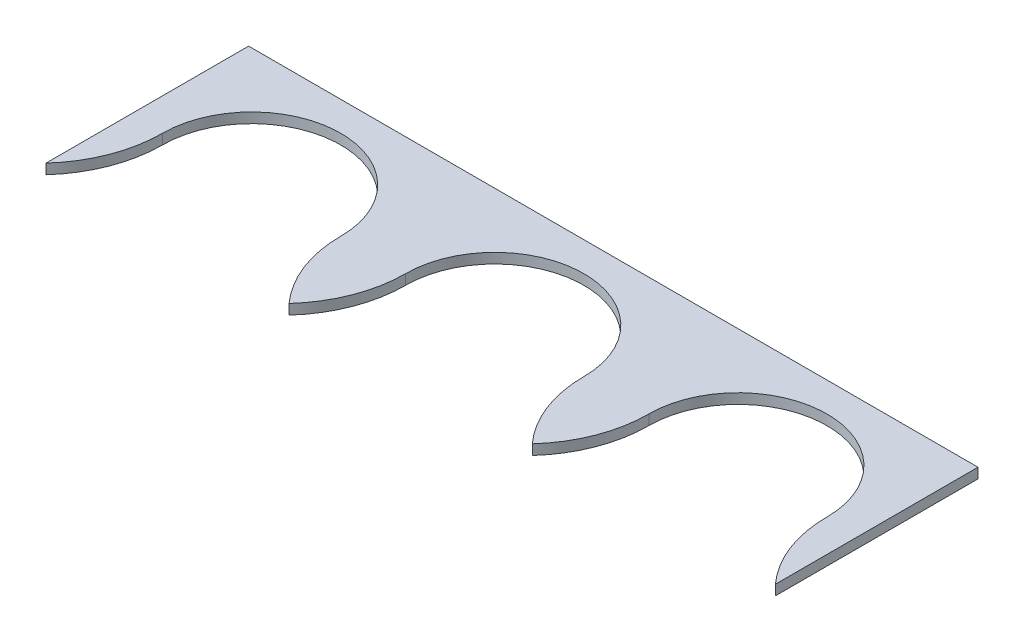
SolidWorks part; units mm, degrees
ref_plane "Front Plane" through (0, 0, 0) normal (0, 0, 1) x (1, 0, 0)
ref_plane "Top Plane" through (0, 0, 0) normal (0, 1, 0) x (1, 0, 0)
ref_plane "Right Plane" through (0, 0, 0) normal (1, 0, 0) x (0, 0, -1)
sketch "Sketch1" plane through (0, 0, 0) normal (0, 1, 0) x (1, 0, 0)
  line L0 (31.9058, -90.254) -> (31.9058, 39.921)
  line L1 (-120.4942, 39.921) -> (336.7058, 39.921)
  line L2 (-120.4942, 39.921) -> (-120.4942, -90.254)
  line L3 (-120.4942, -90.254) -> (336.7058, -90.254)
  line L4 (336.7058, 39.921) -> (336.7058, -90.254)
  line L5 (184.3058, -90.254) -> (184.3058, 39.921)
  circle A0 centre (-44.2942, -34.374) radius 55.88
  circle A1 centre (108.1058, -34.374) radius 55.88
  circle A2 centre (260.5058, -34.374) radius 55.88
  arc A3 (-100.1742, -34.374) -> (-120.4942, -87.079) centre (-178.686, -34.374) cw
  arc A4 (11.5858, -34.374) -> (31.9058, -87.079) centre (90.0976, -34.374) ccw
  arc A5 (52.2258, -34.374) -> (31.9058, -87.079) centre (-26.286, -34.374) cw
  arc A6 (163.9858, -34.374) -> (184.3058, -87.079) centre (242.4976, -34.374) ccw
  arc A7 (204.6258, -34.374) -> (184.3058, -87.079) centre (126.114, -34.374) cw
  arc A8 (316.3858, -34.374) -> (336.7058, -87.079) centre (394.8976, -34.374) ccw
  dimension "D3" = 111.76
  dimension "D4" = 111.76
  dimension "D5" = 111.76
  dimension "D1" = 457.2
  dimension "D2" = 130.175
  dimension "D6" = 152.4
  dimension "D7" = 152.4
  dimension "D8" = 76.2
  dimension "D9" = 76.2
  dimension "D10" = 76.2
  dimension "D11" = 3.175
  dimension "D12" = 3.175
  dimension "D17" = 3.175
  dimension "D18" = 3.175
extrude "Boss-Extrude1" add sketch "Sketch1" against normal blind 6.35
